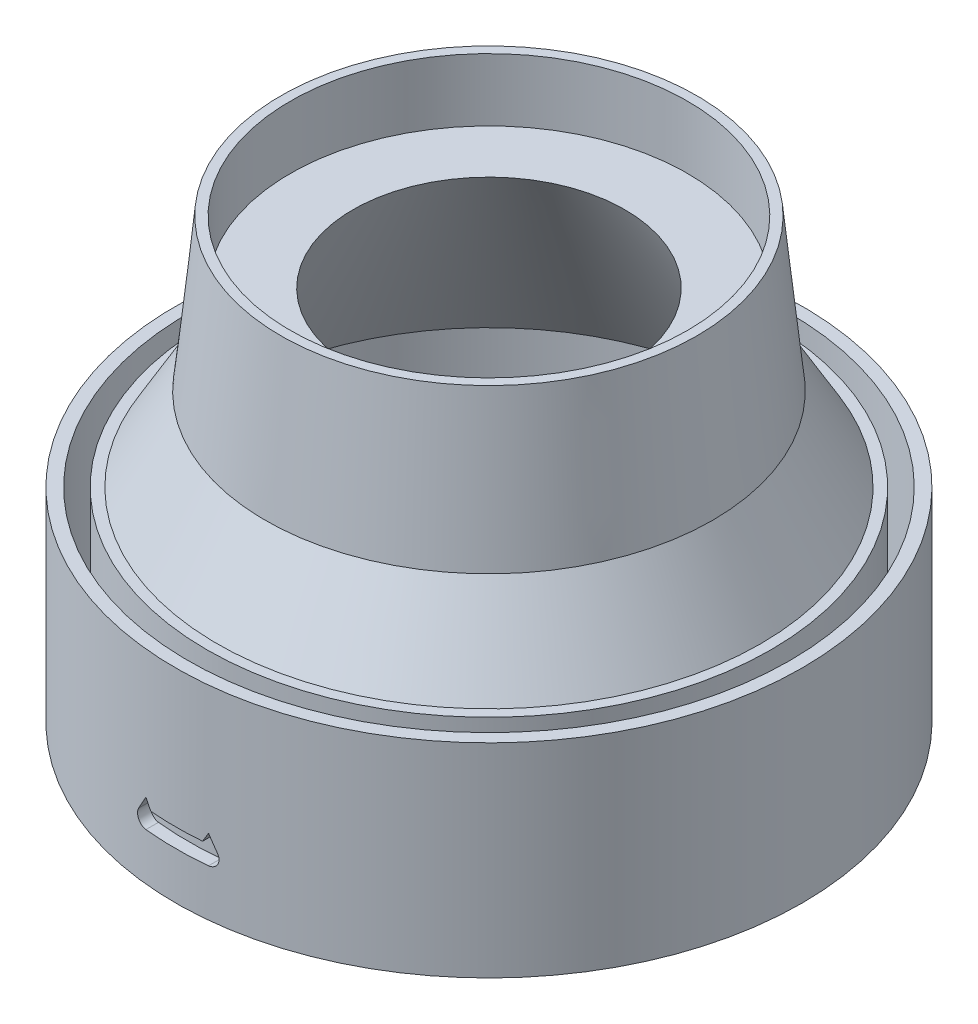
SolidWorks part; units mm, degrees
material "ABS"
ref_plane "Спереди" through (0, 0, 0) normal (0, 0, 1) x (1, 0, 0)
ref_plane "Сверху" through (0, 0, 0) normal (0, 1, 0) x (1, 0, 0)
ref_plane "Справа" through (0, 0, 0) normal (1, 0, 0) x (0, 0, -1)
sketch "Эскиз1" plane through (0, 0, 0) normal (0, 0, 1) x (1, 0, 0)
  line L0 (21.7, 60) -> (31.7, 60)
  line L1 (43.3506, 32.5) -> (35.7, 45.7513)
  line L2 (50, 0) -> (42, 0)
  line L3 (21.7, 60) -> (42, 24.8394)
  line L4 (43.3506, 32.5) -> (45, 32.5)
  line L5 (50, 0) -> (50, 32.5)
  line L6 (50, 32.5) -> (48, 32.5)
  line L7 (48, 32.5) -> (48, 2.5)
  line L8 (48, 2.5) -> (45, 2.5)
  line L9 (45, 2.5) -> (45, 32.5)
  line L10 (0, 4) -> (0, 0) construction
  line L11 (35.7, 45.7513) -> (33.2, 70)
  line L12 (42, 0) -> (42, 24.8394)
  line L19 (31.7, 60) -> (31.7, 70)
  line L20 (31.7, 70) -> (33.2, 70)
  line L23 (0, 0) -> (0, 50.1567) construction
  line L33 (0, 4) -> (0, 0)
  dimension "D1" = 50
  dimension "D2" = 2
  dimension "D3" = 3
  dimension "D4" = 30
  dimension "D5" = 10
  dimension "D6" = 31.7
  dimension "D7" = 1.5
  dimension "D8" = 30
  dimension "D9" = 60
  dimension "D10" = 3
  dimension "D11" = 10
  dimension "D12" = 60
  dimension "D13" = 5
  dimension "D14" = 4
revolve "Повернуть1" add sketch "Эскиз1" angle 360 about L10
sketch "Эскиз3" plane through (0, 0, 0) normal (0, 0, 1) x (1, 0, 0)
  line L0 (3.701, 9.7818) -> (5, 12.0318)
  line L1 (5, 12.0318) -> (6.299, 9.7818)
  line L2 (5, 12.0318) -> (5, 7.5318) construction
  line L3 (0, 0) -> (0, 12.0318) construction
  line L4 (-3.701, 9.7818) -> (-5, 12.0318)
  line L5 (-5, 12.0318) -> (-6.299, 9.7818)
  arc A0 (3.701, 9.7818) -> (6.299, 9.7818) centre (5, 9.0318) ccw
  arc A1 (-3.701, 9.7818) -> (-6.299, 9.7818) centre (-5, 9.0318) cw
  dimension "D1" = 1.5
  dimension "D2" = 60
  dimension "D3" = 5
extrude "Вырез под контру" cut sketch "Эскиз3" against normal mid plane 207.6
ref_plane "Плоскость4" through (0, 0, -60) normal (0, 0, 1) x (1, 0, 0)
sketch "Эскиз4" plane through (0, 0, -60) normal (0, 0, 1) x (1, 0, 0)
  line L0 (-5, 10.5318) -> (5, 10.5318)
  line L1 (-5, 7.5318) -> (5, 7.5318)
  arc A0 (-5, 7.5318) -> (-5, 10.5318) centre (-5, 9.0318) cw
  arc A1 (-6.299, 9.7818) -> (-3.701, 9.7818) centre (-5, 9.0318) ccw construction
  arc A2 (3.701, 9.7818) -> (6.299, 9.7818) centre (5, 9.0318) ccw construction
  arc A3 (5, 7.5318) -> (5, 10.5318) centre (5, 9.0318) ccw
extrude "Вырез-Вытянуть3" cut sketch "Эскиз4" along normal up to surface (12.2611 mm away)
mirror "Зеркальное отражение1" about plane through (0, 0, 0) normal (0, 0, 1) of "Вырез-Вытянуть3"
